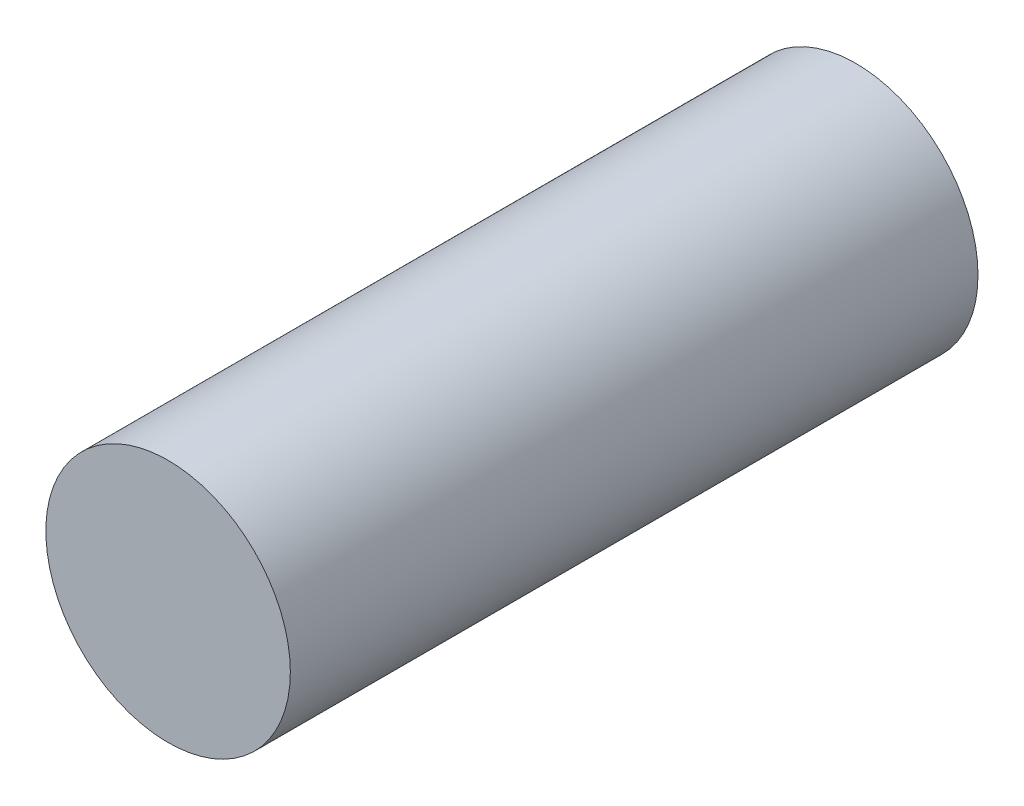
SolidWorks part; units mm, degrees
ref_plane "前视基准面" through (0, 0, 0) normal (0, 0, 1) x (1, 0, 0)
ref_plane "上视基准面" through (0, 0, 0) normal (0, 1, 0) x (1, 0, 0)
ref_plane "右视基准面" through (0, 0, 0) normal (1, 0, 0) x (0, 0, -1)
other "Configuration Table"
sketch "草图1" plane through (0, 0, 0) normal (0, 0, 1) x (1, 0, 0)
  circle A0 centre (0, 0) radius 80
  dimension "D1" = 160
extrude "凸台-拉伸1" add sketch "草图1" along normal blind 450
